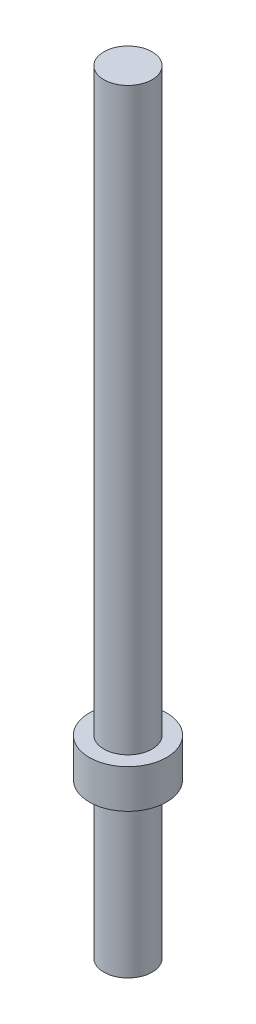
SolidWorks part; units mm, degrees
ref_plane "Front Plane" through (0, 0, 0) normal (0, 0, 1) x (1, 0, 0)
ref_plane "Top Plane" through (0, 0, 0) normal (0, 1, 0) x (1, 0, 0)
ref_plane "Right Plane" through (0, 0, 0) normal (1, 0, 0) x (0, 0, -1)
sketch "Sketch1" plane through (0, 0, 0) normal (0, 1, 0) x (1, 0, 0)
  circle A0 centre (0, 0) radius 2.5
extrude "Boss-Extrude1" add sketch "Sketch1" along normal blind 60
sketch "Sketch2" plane through (0, 0, 0) normal (0, 1, 0) x (1, 0, 0)
  circle A0 centre (0, 0) radius 4
extrude "Boss-Extrude2" add sketch "Sketch2" against normal blind 4
sketch "Sketch3" plane through (0, 0, 0) normal (0, 1, 0) x (1, 0, 0)
  circle A0 centre (0, 0) radius 2.5
extrude "Boss-Extrude3" add sketch "Sketch3" against normal blind 20
